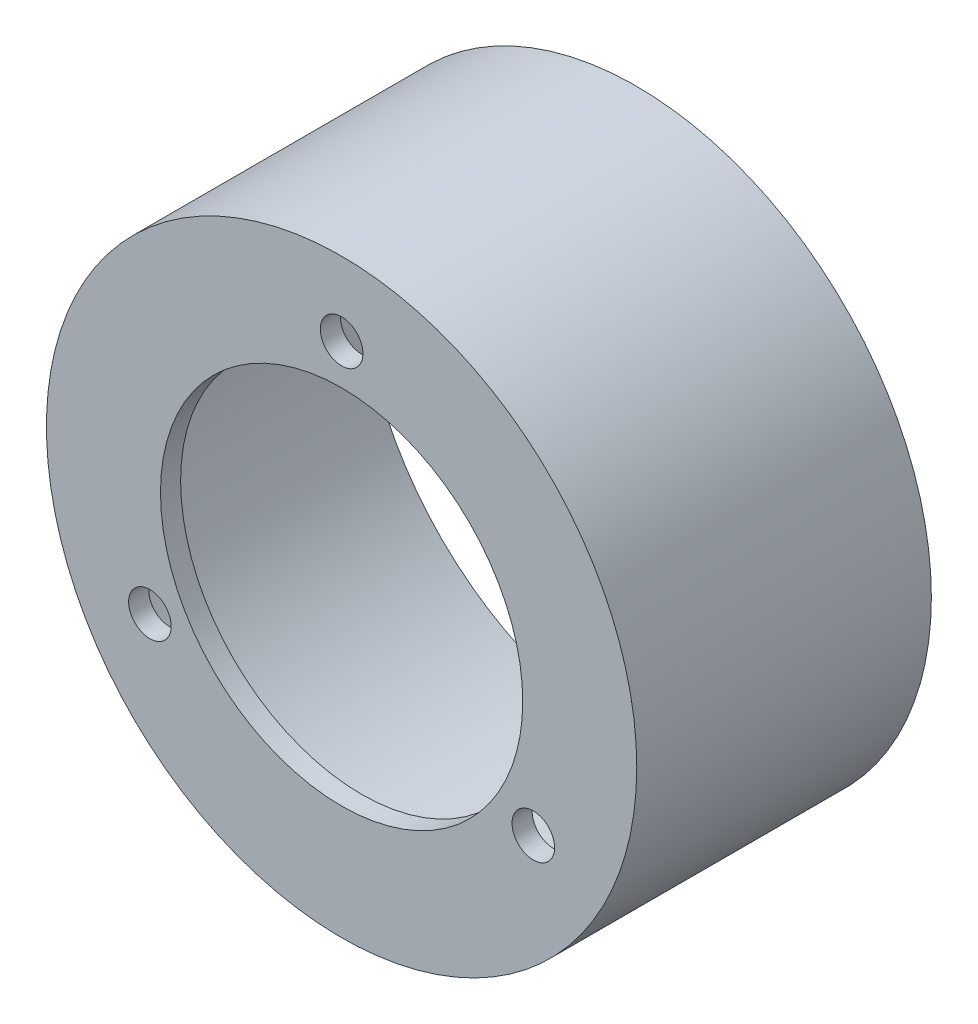
SolidWorks part; units mm, degrees
material "Polyetheretherketone (PEEK)"
ref_plane "Front Plane" through (0, 0, 0) normal (0, 0, 1) x (1, 0, 0)
ref_plane "Top Plane" through (0, 0, 0) normal (0, 1, 0) x (1, 0, 0)
ref_plane "Right Plane" through (0, 0, 0) normal (1, 0, 0) x (0, 0, -1)
sketch "Sketch1" plane through (0, 0, 0) normal (0, 0, 1) x (1, 0, 0)
  circle A0 centre (0, 0) radius 20.5
  circle A1 centre (0, 0) radius 13.5
  circle A2 centre (0, 16.5) radius 1.5875
  circle A3 centre (14.2894, -8.25) radius 1.5875
  circle A4 centre (-14.2894, -8.25) radius 1.5875
  circle A5 centre (0, 0) radius 16.5 construction
  circle A6 centre (14.2894, 8.25) radius 1.5875
  circle A7 centre (14.2894, -8.25) radius 1.5875
  circle A8 centre (0, -16.5) radius 1.5875
  circle A9 centre (-14.2894, -8.25) radius 1.5875
  circle A10 centre (-14.2894, 8.25) radius 1.5875
  dimension "D1" = 27
  dimension "D2" = 3.175
  dimension "D4" = 41
  dimension "D3" = 33
  dimension "D5" = 3
  dimension "D6" = 6
extrude "Extrude1" add sketch "Sketch1" along normal blind 1.5 contours A0 A10 A8 A6 A4 A3 A2 A1 | A10 | A6 | A8
sketch "Sketch2" plane through (0, 0, 1.5) normal (0, 0, 1) x (1, 0, 0)
  circle A0 centre (0, 0) radius 22
  circle A2 centre (0, 0) radius 20.5
  circle A3 centre (0, 0) radius 20.5
  circle A4 centre (0, 0) radius 20.5
  dimension "D1" = 0
  dimension "D2" = 1.5
extrude "Boss-Extrude1" add sketch "Sketch2" against normal blind 21.9577 contours A0 A2
